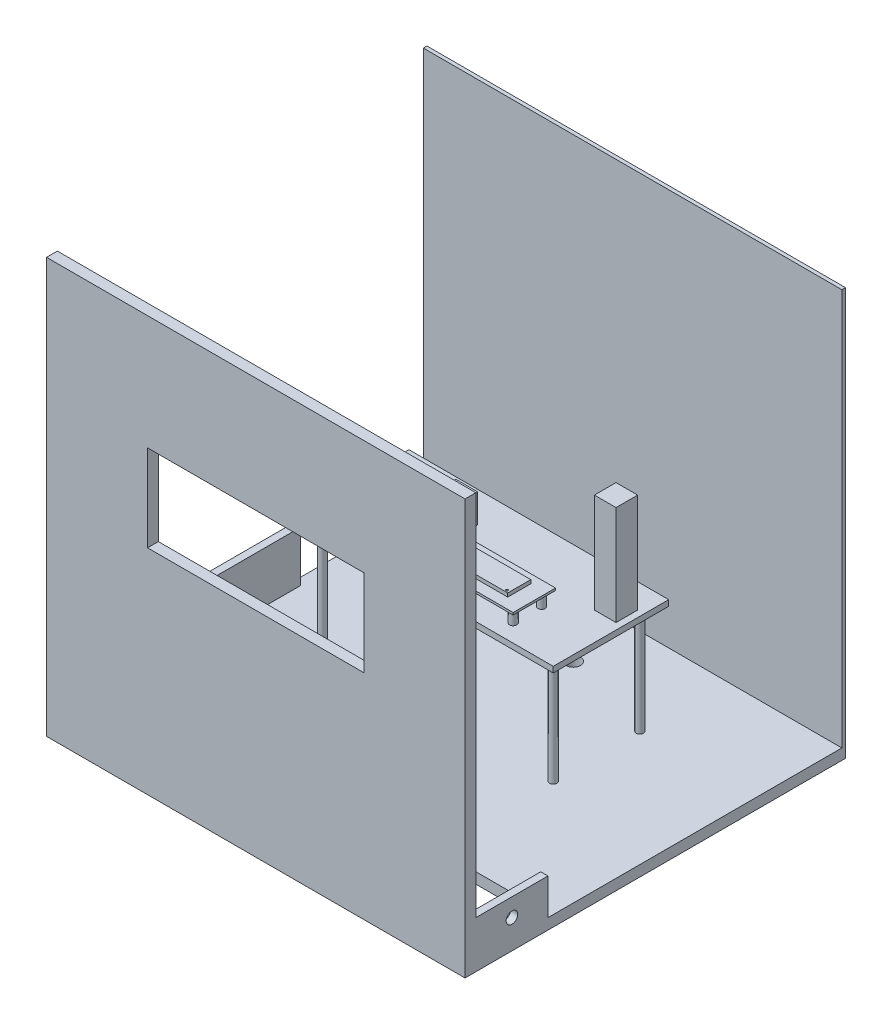
SolidWorks part; units mm, degrees
ref_plane "前视基准面" through (0, 0, 0) normal (0, 0, 1) x (1, 0, 0)
ref_plane "上视基准面" through (0, 0, 0) normal (0, 1, 0) x (1, 0, 0)
ref_plane "右视基准面" through (0, 0, 0) normal (1, 0, 0) x (0, 0, -1)
sketch "草图1" plane through (0, 0, 0) normal (0, 0, 1) x (1, 0, 0)
  line L1 (-90, 0) -> (490, 0)
  line L2 (-90, 0) -> (-90, 560)
  line L3 (-90, 560) -> (490, 560)
  line L4 (490, 0) -> (490, 560)
  line L8 (200, 0) -> (200, 401.3206) construction
  line L9 (200, 401.3206) -> (350, 401.3206)
  line L10 (350, 401.3206) -> (350, 281.3206)
  line L11 (350, 281.3206) -> (50, 281.3206)
  line L12 (50, 281.3206) -> (50, 401.3206)
  line L13 (50, 401.3206) -> (200, 401.3206)
extrude "凸台-拉伸1" add sketch "草图1" along normal blind 15
ref_plane "基准面4" through (0, 0, 0) normal (0, -1, 0) x (1, 0, 0)
sketch "草图3" plane through (0, 0, 0) normal (0, -1, 0) x (1, 0, 0)
  line L0 (-90, 15) -> (490, 15)
  line L1 (490, 15) -> (490, -485.0571)
  line L2 (490, -485.0571) -> (-90, -485.0571)
  line L3 (-90, -485.0571) -> (-90, 15)
extrude "凸台-拉伸2" add sketch "草图3" along normal blind 15 separate body
sketch "草图4" plane through (0, -15, 0) normal (0, -1, 0) x (1, 0, 0)
  line L0 (380, -105.0571) -> (380, -35.0571)
  line L2 (438, -105.0571) -> (380, -105.0571)
  line L4 (200, -35.0571) -> (200, -485.0571) construction
  line L5 (-90, -485.0571) -> (490, -485.0571) construction
  line L6 (20, -35.0571) -> (-38, -35.0571)
  line L7 (-38, -35.0571) -> (-38, -105.0571)
  line L8 (-38, -105.0571) -> (20, -105.0571)
  line L9 (20, -105.0571) -> (20, -35.0571)
  line L10 (438, -35.0571) -> (438, -105.0571)
  line L11 (380, -35.0571) -> (438, -35.0571)
  circle A0 centre (200, -425.0571) radius 10
  dimension "D3" = 380
  dimension "D1" = 180
  dimension "D2" = 58
  dimension "D4" = 70
  dimension "D5" = 60
extrude "切除-拉伸1" cut sketch "草图4" against normal blind 15
sketch "草图5" plane through (0, -15, 0) normal (0, -1, 0) x (1, 0, 0)
  line L1 (180, -445.0571) -> (220, -445.0571)
  line L2 (180, -445.0571) -> (180, -405.0571)
  line L3 (180, -405.0571) -> (220, -405.0571)
  line L4 (220, -445.0571) -> (220, -405.0571)
  line L5 (180, -445.0571) -> (220, -405.0571) construction
  line L6 (180, -405.0571) -> (220, -445.0571) construction
  circle A0 centre (200, -425.0571) radius 10
  point P0 (200, -425.0571)
  dimension "D1" = 40
  dimension "D2" = 40
extrude "凸台-拉伸3" add sketch "草图5" along normal blind 7
sketch "草图6" plane through (-90, 0, 0) normal (-1, 0, 0) x (0, 0, 1)
  line L1 (0, 0) -> (-100, 0)
  line L2 (0, 0) -> (0, 50)
  line L3 (0, 50) -> (-100, 50)
  line L4 (-100, 0) -> (-100, 50)
  circle A0 centre (-50, 25) radius 8
extrude "凸台-拉伸4" add sketch "草图6" against normal blind 10
sketch "草图7" plane through (490, 0, 0) normal (1, 0, 0) x (0, 0, -1)
  line L1 (100, 50) -> (0, 50)
  line L2 (100, 50) -> (100, 0)
  line L3 (100, 0) -> (0, 0)
  line L4 (0, 50) -> (0, 0)
  circle A0 centre (50, 25) radius 8
extrude "凸台-拉伸5" add sketch "草图7" against normal blind 10
sketch "草图8" plane through (0, 0, -485.0571) normal (0, 0, -1) x (-1, 0, 0)
  line L1 (-490, -15) -> (90, -15)
  line L2 (-490, -15) -> (-490, 0)
  line L3 (-490, 0) -> (90, 0)
  line L4 (90, -15) -> (90, 0)
extrude "凸台-拉伸6" add sketch "草图8" along normal blind 27.2
sketch "草图9" plane through (0, 0, 0) normal (0, 1, 0) x (1, 0, 0)
  line L0 (490, 512.2571) -> (490, 100) construction
  line L1 (-90, 512.2571) -> (490, 512.2571)
  line L2 (-90, 512.2571) -> (-90, 507.2571)
  line L3 (-90, 507.2571) -> (490, 507.2571)
  line L4 (490, 512.2571) -> (490, 507.2571)
  dimension "D1" = 5
extrude "凸台-拉伸7" add sketch "草图9" along normal blind 550
sketch "草图10" plane through (0, 0, 0) normal (0, 1, 0) x (1, 0, 0)
  line L0 (-90, 507.2571) -> (490, 507.2571) construction
  line L1 (10, 387.2571) -> (10, 267.2571) construction
  line L2 (10, 267.2571) -> (330, 267.2571) construction
  line L3 (330, 267.2571) -> (330, 387.2571) construction
  line L4 (330, 387.2571) -> (10, 387.2571) construction
  line L5 (-90, 100) -> (-90, 507.2571) construction
  circle A0 centre (10, 387.2571) radius 5
  circle A1 centre (330, 387.2571) radius 5
  circle A2 centre (10, 267.2571) radius 5
  circle A3 centre (330, 267.2571) radius 5
  dimension "D2" = 10
  dimension "D3" = 100
  dimension "D1" = 120
  dimension "D4" = 320
  dimension "D5" = 120
extrude "凸台-拉伸8" add sketch "草图10" along normal blind 150
sketch "草图11" plane through (0, 150, 0) normal (0, 1, 0) x (1, 0, 0)
  line L1 (-10, 407.2571) -> (350, 407.2571)
  line L2 (-10, 407.2571) -> (-10, 247.2571)
  line L3 (-10, 247.2571) -> (350, 247.2571)
  line L4 (350, 407.2571) -> (350, 247.2571)
  line L5 (10, 387.2571) -> (330, 387.2571) construction
  line L6 (330, 387.2571) -> (330, 267.2571) construction
  line L7 (330, 267.2571) -> (10, 267.2571) construction
  line L8 (10, 267.2571) -> (10, 387.2571) construction
  dimension "D1" = 20
  dimension "D2" = 20
  dimension "D3" = 20
  dimension "D4" = 20
extrude "凸台-拉伸9" add sketch "草图11" along normal blind 8
sketch "草图12" plane through (0, 158, 0) normal (0, 1, 0) x (1, 0, 0)
  line L0 (-10, 407.2571) -> (-10, 247.2571) construction
  line L1 (98, 364.2571) -> (128, 364.2571)
  line L2 (98, 364.2571) -> (98, 334.2571)
  line L3 (98, 334.2571) -> (128, 334.2571)
  line L4 (128, 364.2571) -> (128, 334.2571)
  line L5 (350, 407.2571) -> (-10, 407.2571) construction
  line L6 (350, 247.2571) -> (350, 407.2571) construction
  line L7 (350, 393.053) -> (320, 393.053) construction
  line L8 (350, 393.053) -> (350, 363.053) construction
  line L9 (350, 363.053) -> (320, 363.053) construction
  line L10 (320, 393.053) -> (320, 363.053) construction
  dimension "D1" = 30
  dimension "D2" = 30
  dimension "D3" = 108
  dimension "D4" = 43
  dimension "D5" = 30
  dimension "D6" = 30
extrude "凸台-拉伸10" add sketch "草图12" along normal blind 40
sketch "草图13" plane through (0, 158, 0) normal (0, 1, 0) x (1, 0, 0)
  line L1 (341, 373.2571) -> (311, 373.2571)
  line L2 (341, 373.2571) -> (341, 343.2571)
  line L3 (341, 343.2571) -> (311, 343.2571)
  line L4 (311, 373.2571) -> (311, 343.2571)
  line L5 (350, 407.2571) -> (-10, 407.2571) construction
  line L6 (350, 247.2571) -> (350, 407.2571) construction
  dimension "D1" = 30
  dimension "D2" = 30
  dimension "D3" = 34
  dimension "D4" = 9
extrude "凸台-拉伸11" add sketch "草图13" along normal blind 138
sketch "草图14" plane through (-90, 0, 0) normal (-1, 0, 0) x (0, 0, 1)
  line L0 (-100, 0) -> (-507.2571, 0) construction
  line L1 (-327.2571, 0) -> (-200, 0)
  line L2 (-327.2571, 0) -> (-327.2571, 70)
  line L3 (-327.2571, 70) -> (-200, 70)
  line L4 (-200, 0) -> (-200, 70)
  line L5 (-507.2571, 550) -> (-507.2571, 0) construction
  line L6 (0, 560) -> (0, 50) construction
  dimension "D1" = 180
  dimension "D2" = 200
  dimension "D3" = 70
extrude "凸台-拉伸12" add sketch "草图14" against normal blind 10
sketch "草图15" plane through (-90, 0, 0) normal (-1, 0, 0) x (0, 0, 1)
  circle A0 centre (-263.6285, 35) radius 10
  circle A1 centre (-263.6285, 35) radius 7
  circle A2 centre (-263.6285, 35) radius 2.5
extrude "凸台-拉伸13" add sketch "草图15" along normal blind 3 contours A0 A1 | A2
fillet "圆角2" radius 2 2 edges at (-93, 35, -261.1285) (-93, 35, -253.6285)
sketch "草图16" plane through (0, 158, 0) normal (0, 1, 0) x (1, 0, 0)
  circle A0 centre (171.7902, 271.6404) radius 5
  circle A1 centre (270.1292, 271.6404) radius 5
  circle A2 centre (171.7902, 310.9187) radius 5
  circle A3 centre (270.1292, 310.9187) radius 5
extrude "凸台-拉伸14" add sketch "草图16" along normal blind 20
sketch "草图17" plane through (0, 178, 0) normal (0, 1, 0) x (1, 0, 0)
  line L1 (161.1932, 319.7835) -> (280.6507, 319.7835)
  line L2 (161.1932, 319.7835) -> (161.1932, 261.0066)
  line L3 (161.1932, 261.0066) -> (280.6507, 261.0066)
  line L4 (280.6507, 319.7835) -> (280.6507, 261.0066)
extrude "凸台-拉伸15" add sketch "草图17" along normal blind 3
sketch "草图18" plane through (0, 181, 0) normal (0, 1, 0) x (1, 0, 0)
  line L1 (180.3971, 307.7445) -> (258.4133, 307.7445)
  line L2 (180.3971, 307.7445) -> (180.3971, 275.748)
  line L3 (180.3971, 275.748) -> (258.4133, 275.748)
  line L4 (258.4133, 307.7445) -> (258.4133, 275.748)
  circle A0 centre (184.2999, 304.1066) radius 1.406
  circle A1 centre (184.2999, 278.5171) radius 1.5374
  circle A2 centre (254.5071, 278.5171) radius 1.4998
extrude "凸台-拉伸16" add sketch "草图18" along normal blind 5
